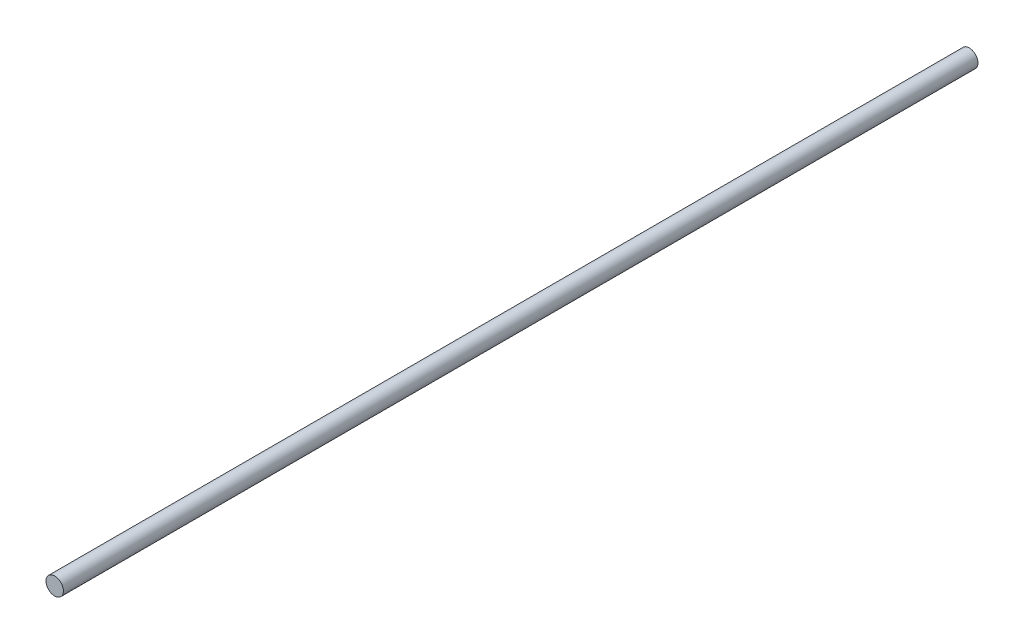
SolidWorks part; units mm, degrees
ref_plane "Front Plane" through (0, 0, 0) normal (0, 0, 1) x (1, 0, 0)
ref_plane "Top Plane" through (0, 0, 0) normal (0, 1, 0) x (1, 0, 0)
ref_plane "Right Plane" through (0, 0, 0) normal (1, 0, 0) x (0, 0, -1)
sketch "Sketch1" plane through (0, 0, 0) normal (0, 0, 1) x (1, 0, 0)
  circle A0 centre (0, 0) radius 4
  dimension "D1" = 8
extrude "Boss-Extrude1" add sketch "Sketch1" along normal blind 420
